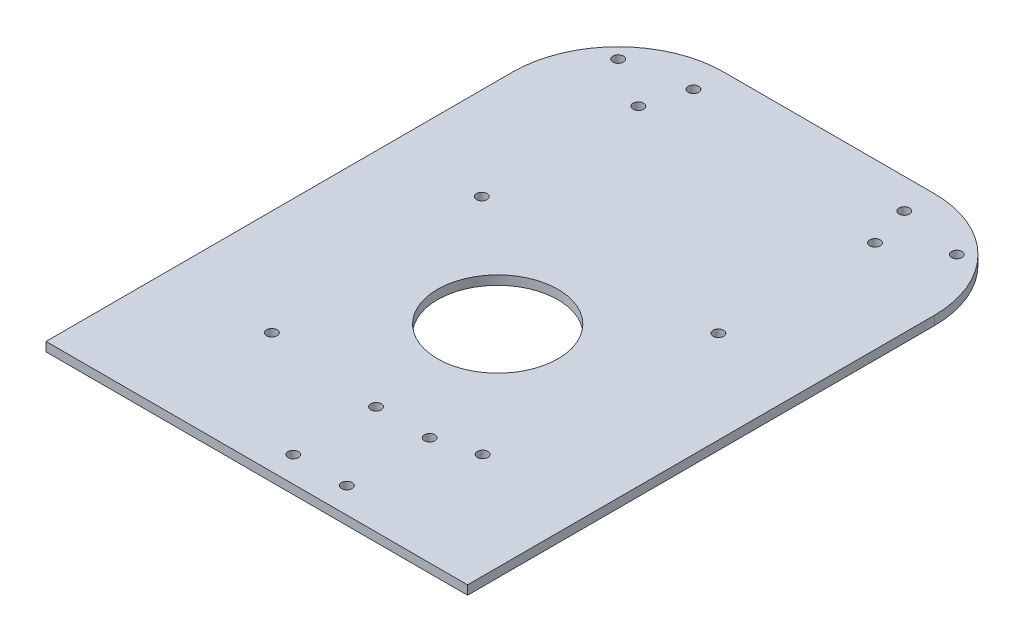
SolidWorks part; units mm, degrees
ref_plane "前视基准面" through (0, 0, 0) normal (0, 0, 1) x (1, 0, 0)
ref_plane "上视基准面" through (0, 0, 0) normal (0, 1, 0) x (1, 0, 0)
ref_plane "右视基准面" through (0, 0, 0) normal (1, 0, 0) x (0, 0, -1)
sketch "草图1" plane through (0, 0, 0) normal (0, 1, 0) x (1, 0, 0)
  line L1 (-70, 110) -> (70, 110)
  line L2 (-70, 110) -> (-70, -110)
  line L3 (-70, -110) -> (70, -110)
  line L4 (70, 110) -> (70, -110)
  line L5 (-70, 110) -> (70, -110) construction
  line L6 (-70, -110) -> (70, 110) construction
  circle A8 centre (21.4, -74) radius 1.75 construction
  circle A9 centre (21.4, -101.5) radius 1.75 construction
  circle A10 centre (3.6, -101.5) radius 1.75 construction
  circle A11 centre (3.6, -74) radius 1.75 construction
  circle A12 centre (21.4, -74) radius 1.75
  circle A13 centre (21.4, -101.5) radius 1.75
  circle A14 centre (3.6, -101.5) radius 1.75
  circle A15 centre (3.6, -74) radius 1.75
  point P0 (0, 0)
  dimension "D1" = 140
  dimension "D2" = 220
  dimension "D3" = 17.8
extrude "凸台-拉伸1" add sketch "草图1" along normal blind 3
sketch "草图2" plane through (0, 3, 0) normal (0, 1, 0) x (1, 0, 0)
  line L0 (-35, 70) -> (35, 70) construction
  line L2 (-35, 70) -> (-35, -70) construction
  line L3 (-35, -70) -> (35, -70) construction
  line L4 (35, 70) -> (35, -70) construction
  line L5 (-35, 70) -> (35, -70) construction
  line L6 (-35, -70) -> (35, 70) construction
  line L7 (0, 0) -> (0, -30) construction
  circle A0 centre (-35, 70) radius 1.75
  circle A1 centre (35, 70) radius 1.75
  circle A2 centre (-35, -70) radius 1.75
  circle A3 centre (35, -70) radius 1.75
  circle A5 centre (0, -30) radius 20
  point P0 (0, 0)
  dimension "D3" = 3.5
  dimension "D4" = 40
  dimension "D5" = 30
  dimension "D1" = 70
  dimension "D2" = 140
extrude "切除-拉伸1" cut sketch "草图2" against normal through all
sketch "草图3" plane through (0, 3, 0) normal (0, 1, 0) x (1, 0, 0)
  line L0 (70, -110) -> (70, 110) construction
  line L1 (70, 110) -> (-70, 110) construction
  line L2 (-70, 110) -> (-70, -110) construction
  line L3 (70, -110) -> (70, 45) construction
  line L4 (70, 110) -> (-70, 110) construction
  line L5 (-70, 45) -> (-70, -110) construction
  line L6 (-35, 80) -> (35, 80)
  line L7 (-70, 110) -> (-70, 80) construction
  line L8 (70, 80) -> (70, 110) construction
  line L9 (-70, 45) -> (-70, 110)
  line L10 (-70, 110) -> (70, 110)
  line L11 (70, 110) -> (70, 45)
  line L12 (-35, 70) -> (35, 70) construction
  line L13 (0, 70) -> (0, 30) construction
  line L14 (-70, 45) -> (-35, 45) construction
  line L15 (-39.3, 56) -> (39.3, 56) construction
  line L16 (-39.3, 56) -> (-39.3, 4) construction
  line L17 (-39.3, 4) -> (39.3, 4) construction
  line L18 (39.3, 56) -> (39.3, 4) construction
  line L19 (-39.3, 56) -> (39.3, 4) construction
  line L20 (-39.3, 4) -> (39.3, 56) construction
  line L21 (-35, 45) -> (-56.2132, 66.2132) construction
  arc A0 (-70, 45) -> (-35, 80) centre (-35, 45) cw
  arc A1 (70, 45) -> (35, 80) centre (35, 45) ccw
  circle A2 centre (-39.3, 56) radius 1.75
  circle A3 centre (-39.3, 4) radius 1.75
  circle A4 centre (39.3, 4) radius 1.75
  circle A5 centre (39.3, 56) radius 1.75
  circle A6 centre (-56.2132, 66.2132) radius 1.75
  circle A7 centre (56.2132, 66.2132) radius 1.75
  dimension "D2" = 35
  dimension "D3" = 35
  dimension "D7" = 3.5
  dimension "D8" = 45
  dimension "D10" = 3.5
  dimension "D1" = 30
  dimension "D4" = 78.6
  dimension "D5" = 52
  dimension "D6" = 40
  dimension "D9" = 30
extrude "切除-拉伸2" cut sketch "草图3" against normal through all
